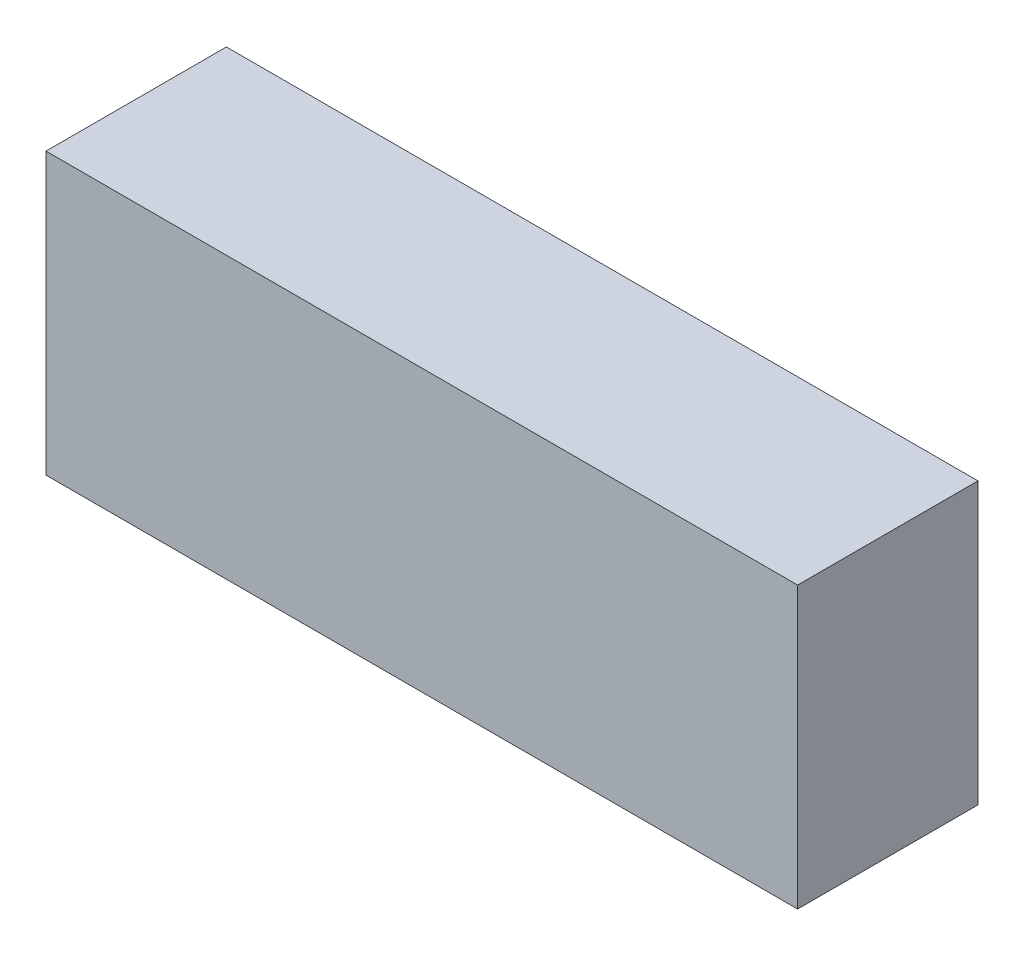
SolidWorks part; units mm, degrees
ref_plane "Front Plane" through (0, 0, 0) normal (0, 0, 1) x (1, 0, 0)
ref_plane "Top Plane" through (0, 0, 0) normal (0, 1, 0) x (1, 0, 0)
ref_plane "Right Plane" through (0, 0, 0) normal (1, 0, 0) x (0, 0, -1)
sketch "Sketch1" plane through (0, 0, 0) normal (0, 1, 0) x (1, 0, 0)
  line L1 (37.5, -9) -> (-37.5, -9)
  line L2 (37.5, -9) -> (37.5, 9)
  line L3 (37.5, 9) -> (-37.5, 9)
  line L4 (-37.5, -9) -> (-37.5, 9)
  line L5 (0, 9) -> (0, -9) construction
  line L6 (37.5, 0) -> (-37.5, 0) construction
  point P0 (0, 0)
  dimension "D1" = 18
  dimension "D2" = 75
extrude "Boss-Extrude1" add sketch "Sketch1" along normal blind 28
